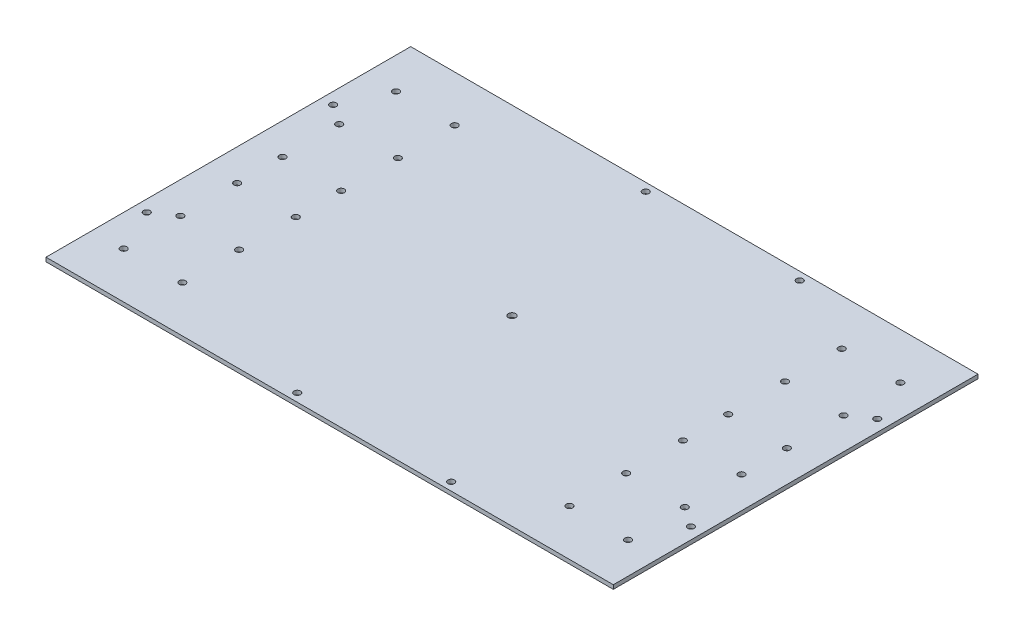
SolidWorks part; units mm, degrees
material "1345 Alloy"
ref_plane "Front Plane" through (0, 0, 0) normal (0, 0, 1) x (1, 0, 0)
ref_plane "Top Plane" through (0, 0, 0) normal (0, 1, 0) x (1, 0, 0)
ref_plane "Right Plane" through (0, 0, 0) normal (1, 0, 0) x (0, 0, -1)
other "Center of Mass"
sketch "Sketch2" plane through (0, 0, 0) normal (0, 1, 0) x (1, 0, 0)
  line L1 (-350, 225) -> (350, 225)
  line L2 (-350, 225) -> (-350, -225)
  line L3 (-350, -225) -> (350, -225)
  line L4 (350, 225) -> (350, -225)
  line L5 (-350, 225) -> (350, -225) construction
  line L6 (-350, -225) -> (350, 225) construction
  point P0 (0, 0)
  dimension "D1" = 700
  dimension "D2" = 450
extrude "Boss-Extrude1" add sketch "Sketch2" along normal mid plane 5
sketch "Sketch6" plane through (0, 2.5, 0) normal (0, 1, 0) x (1, 0, 0)
  circle A0 centre (-311.2031, 168) radius 4
  circle A1 centre (-238.7931, 168) radius 4
  circle A2 centre (-238.7931, 98) radius 4
  circle A3 centre (-311.2031, 98) radius 4
  circle A4 centre (-311.2031, 28) radius 4
  circle A5 centre (-238.7931, 28) radius 4
  circle A6 centre (238.7931, 168) radius 4
  circle A7 centre (311.2031, 168) radius 4
  circle A8 centre (311.2031, 98) radius 4
  circle A9 centre (238.7931, 98) radius 4
  circle A10 centre (238.7931, 28) radius 4
  circle A11 centre (311.2031, 28) radius 4
  circle A12 centre (-311.2031, -28) radius 4
  circle A13 centre (-238.7931, -28) radius 4
  circle A14 centre (-238.7931, -98) radius 4
  circle A15 centre (-311.2031, -98) radius 4
  circle A16 centre (-311.2031, -168) radius 4
  circle A17 centre (-238.7931, -168) radius 4
  circle A18 centre (238.7931, -28) radius 4
  circle A19 centre (311.2031, -28) radius 4
  circle A20 centre (311.2031, -98) radius 4
  circle A21 centre (238.7931, -98) radius 4
  circle A22 centre (238.7931, -168) radius 4
  circle A23 centre (311.2031, -168) radius 4
  dimension "D1" = 8
  dimension "D2" = 8
  dimension "D3" = 8
  dimension "D4" = 8
  dimension "D5" = 8
  dimension "D6" = 8
  dimension "D7" = 8
  dimension "D8" = 8
  dimension "D9" = 8
  dimension "D10" = 8
  dimension "D11" = 8
  dimension "D12" = 8
  dimension "D13" = 8
  dimension "D14" = 8
  dimension "D15" = 8
  dimension "D16" = 8
  dimension "D17" = 8
  dimension "D18" = 8
  dimension "D19" = 8
  dimension "D20" = 8
  dimension "D21" = 8
  dimension "D22" = 8
  dimension "D23" = 8
  dimension "D24" = 8
extrude "Cut-Extrude2" cut sketch "Sketch6" against normal through all
sketch "Sketch8" plane through (0, 2.5, 0) normal (0, 1, 0) x (1, 0, 0)
  line L0 (-350, 225) -> (350, -225) construction
  line L1 (350, 225) -> (-350, -225) construction
  circle A0 centre (0, 0) radius 4.5
  dimension "D1" = 9
extrude "Cut-Extrude4" cut sketch "Sketch8" against normal up to next
sketch "Sketch9" plane through (0, 2.5, 0) normal (0, 1, 0) x (1, 0, 0)
  line L0 (-50, -215) -> (140, -215) construction
  line L1 (-50, 215) -> (-50, -215) construction
  line L2 (140, -215) -> (140, 215) construction
  line L5 (-350, 215) -> (-50, 215) construction
  line L6 (-350, 225) -> (-350, -225) construction
  circle A0 centre (-50, -215) radius 4
  circle A1 centre (140, -215) radius 4
  circle A2 centre (-50, 215) radius 4
  circle A3 centre (140, 215) radius 4
  dimension "D1" = 8
  dimension "D2" = 8
  dimension "D3" = 8
  dimension "D4" = 8
  dimension "D5" = 300
  dimension "D6" = 190
extrude "Cut-Extrude5" cut sketch "Sketch9" against normal through all
sketch "Sketch10" plane through (0, 2.5, 0) normal (0, 1, 0) x (1, 0, 0)
  line L0 (-350, 225) -> (-335.68, 225) construction
  line L1 (350, 225) -> (-350, 225) construction
  line L2 (-335.68, 225) -> (-335.68, 115) construction
  line L3 (-350, -225) -> (-335.68, -225) construction
  line L4 (-350, -225) -> (350, -225) construction
  line L5 (-335.68, -225) -> (-335.68, -115) construction
  line L6 (350, 225) -> (335.68, 225) construction
  line L7 (335.68, 225) -> (335.68, 115) construction
  line L8 (350, -225) -> (335.68, -225) construction
  line L9 (335.68, -225) -> (335.68, -115) construction
  circle A0 centre (-335.68, 115) radius 4
  circle A1 centre (-335.68, -115) radius 4
  circle A2 centre (335.68, 115) radius 4
  circle A3 centre (335.68, -115) radius 4
  dimension "D5" = 8
  dimension "D6" = 8
  dimension "D1" = 14.32
  dimension "D2" = 14.32
  dimension "D3" = 110
  dimension "D4" = 110
  dimension "D7" = 14.32
  dimension "D8" = 110
  dimension "D9" = 14.32
  dimension "D10" = 110
extrude "Cut-Extrude6" cut sketch "Sketch10" against normal through all both
